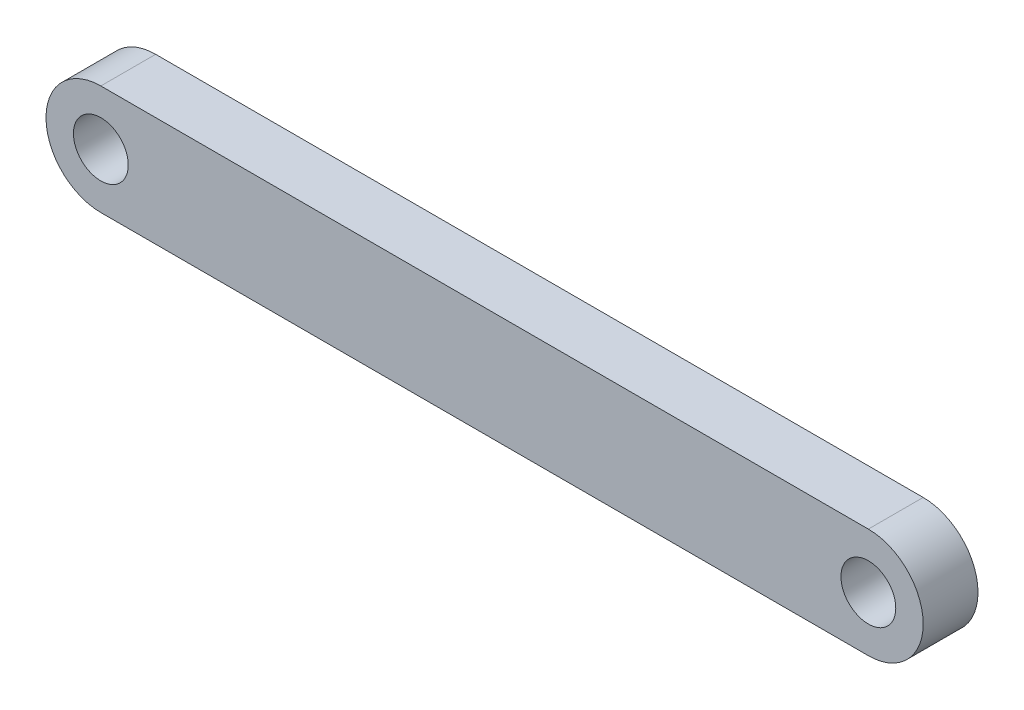
SolidWorks part; units mm, degrees
ref_plane "前视基准面" through (0, 0, 0) normal (0, 0, 1) x (1, 0, 0)
ref_plane "上视基准面" through (0, 0, 0) normal (0, 1, 0) x (1, 0, 0)
ref_plane "右视基准面" through (0, 0, 0) normal (1, 0, 0) x (0, 0, -1)
sketch "草图1" plane through (0, 0, 0) normal (0, 0, 1) x (1, 0, 0)
  line L0 (-69.2213, 27.9862) -> (0.7787, 27.9862)
  line L1 (-69.2213, 17.9862) -> (0.7787, 17.9862)
  arc A0 (-69.2213, 27.9862) -> (-69.2213, 17.9862) centre (-69.2213, 22.9862) ccw
  arc A1 (0.7787, 27.9862) -> (0.7787, 17.9862) centre (0.7787, 22.9862) cw
  dimension "D1" = 70
extrude "凸台-拉伸1" add sketch "草图1" along normal mid plane 5
sketch "草图3" plane through (0, 0, 2.5) normal (0, 0, 1) x (1, 0, 0)
  circle A0 centre (-69.2213, 22.9862) radius 2.5
extrude "切除-拉伸2" cut sketch "草图3" against normal blind 8
sketch "草图5" plane through (0, 0, 2.5) normal (0, 0, 1) x (1, 0, 0)
  circle A0 centre (0.7787, 22.9862) radius 2.5
extrude "切除-拉伸4" cut sketch "草图5" against normal blind 8
